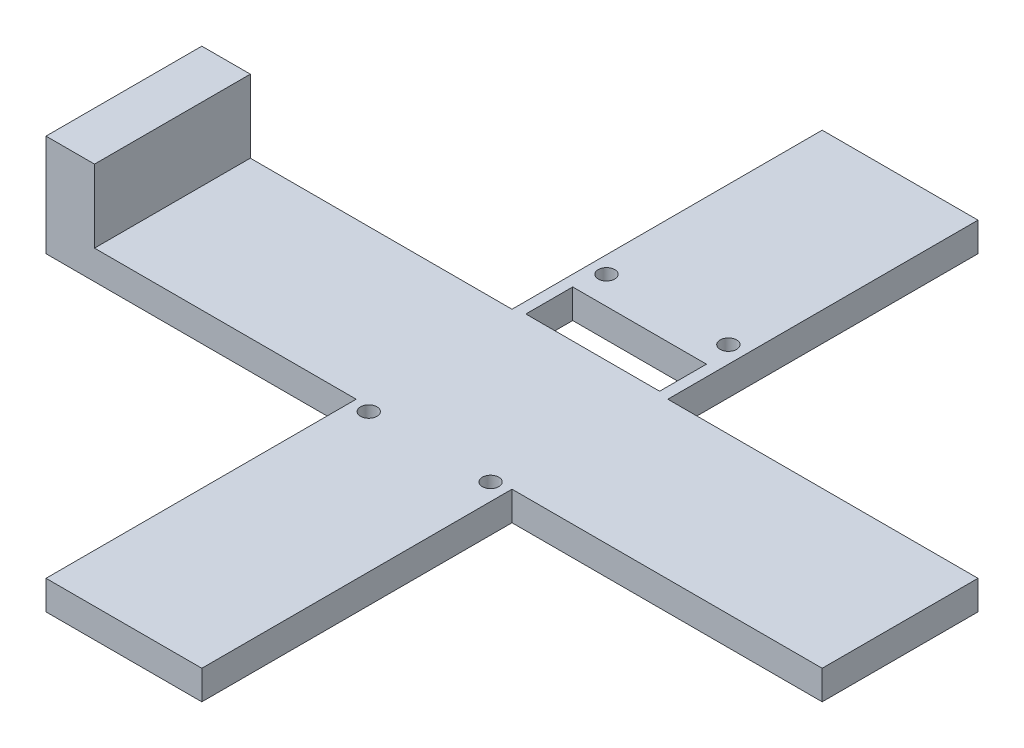
SolidWorks part; units mm, degrees
ref_plane "Front Plane" through (0, 0, 0) normal (0, 0, 1) x (1, 0, 0)
ref_plane "Top Plane" through (0, 0, 0) normal (0, 1, 0) x (1, 0, 0)
ref_plane "Right Plane" through (0, 0, 0) normal (1, 0, 0) x (0, 0, -1)
sketch "Sketch21" plane through (0, 0, 0) normal (0, 1, 0) x (1, 0, 0)
  line L22 (0, 84) -> (-16.06, 84)
  line L23 (-16.06, 84) -> (-16.06, 20.06)
  line L24 (-16.06, 20.06) -> (-80, 20.06)
  line L25 (-80, -12.06) -> (-16.06, -12.06)
  line L26 (-16.06, -12.06) -> (-16.06, -76)
  line L27 (-16.06, -76) -> (0, -76)
  line L28 (0, -76) -> (16.06, -76)
  line L29 (16.06, -76) -> (16.06, -12.06)
  line L30 (16.06, -12.06) -> (80, -12.06)
  line L31 (80, 20.06) -> (16.06, 20.06)
  line L32 (16.06, 20.06) -> (16.06, 84)
  line L33 (16.06, 84) -> (0, 84)
  line L34 (-80, 4) -> (-80, 20.06)
  line L35 (-80, -12.06) -> (-80, 4)
  line L36 (80, 4) -> (80, 20.06)
  line L37 (80, 4) -> (80, -12.06)
  line L38 (13.785, 20.64) -> (-13.785, 20.64)
  line L39 (13.785, 20.64) -> (13.785, 30.3)
  line L40 (13.785, 30.3) -> (-13.785, 30.3)
  line L41 (-13.785, 20.64) -> (-13.785, 30.3)
  circle A0 centre (-12.56, 36.04) radius 1.7
  circle A1 centre (12.56, 36.04) radius 1.7
  circle A2 centre (12.56, -12.97) radius 1.7
  circle A3 centre (-12.56, -12.97) radius 1.7
  point P30 (0, 0)
  dimension "D7" = 3.4
  dimension "D9" = 1.225
  dimension "D10" = 49.01
  dimension "D12" = 10.24
  dimension "D6" = 5.74
  dimension "D11" = 49.01
  dimension "D8" = 1.225
  dimension "D1" = 63.94
  dimension "D2" = 16.06
  dimension "D3" = 27.57
  dimension "D4" = 9.66
  dimension "D5" = 5.74
  dimension "D13" = 16.06
extrude "Boss-Extrude18" add sketch "Sketch21" along normal blind 6
sketch "Sketch22" plane through (0, 6, 0) normal (0, 1, 0) x (1, 0, 0)
  line L0 (-80, -12.06) -> (-16.06, -12.06) construction
  line L1 (-80, 20.06) -> (-70, 20.06)
  line L2 (-80, 20.06) -> (-80, -12.06)
  line L3 (-80, -12.06) -> (-70, -12.06)
  line L4 (-70, 20.06) -> (-70, -12.06)
  dimension "D1" = 10
extrude "Boss-Extrude19" add sketch "Sketch22" along normal blind 15
